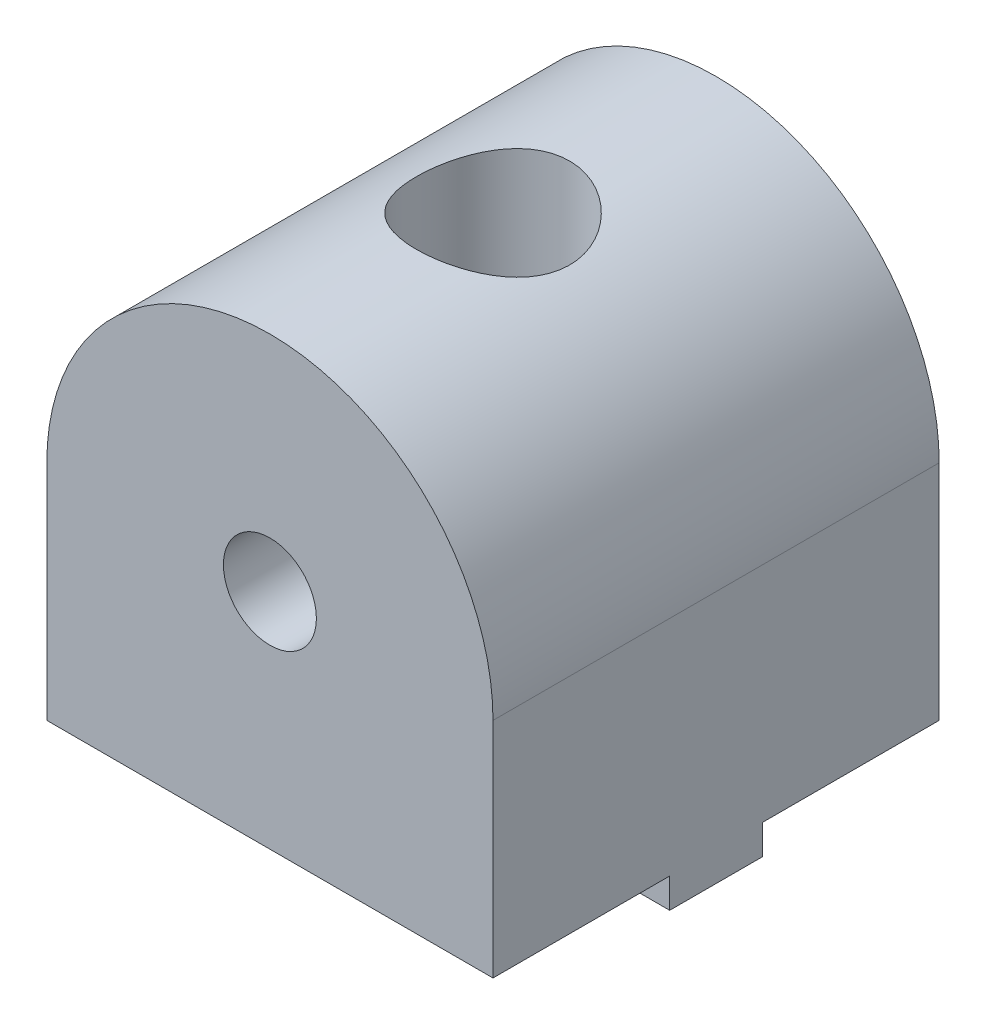
SolidWorks part; units mm, degrees
material "6105-T5 Aluminum"
ref_plane "Front Plane" through (0, 0, 0) normal (0, 0, 1) x (1, 0, 0)
ref_plane "Top Plane" through (0, 0, 0) normal (0, 1, 0) x (1, 0, 0)
ref_plane "Right Plane" through (0, 0, 0) normal (1, 0, 0) x (0, 0, -1)
sketch "Sketch1" plane through (0, 0, 0) normal (0, 0, 1) x (1, 0, 0)
  line L2 (-12.4454, 4.399) -> (-12.4454, -14.651)
  line L3 (-12.4454, -14.651) -> (25.6546, -14.651)
  line L4 (25.6546, 4.399) -> (25.6546, -14.651)
  arc A0 (25.6546, 4.399) -> (-12.4454, 4.399) centre (6.6046, 4.399) ccw
  circle A1 centre (6.6046, 4.399) radius 3.9688
  dimension "D2" = 38.1
extrude "Extrude1" add sketch "Sketch1" along normal blind 38.1
sketch "Sketch2" plane through (0, -14.651, 0) normal (0, -1, 0) x (1, 0, 0)
  line L2 (6.6046, 38.1) -> (6.6046, 0)
  line L3 (6.6046, 38.1) -> (6.6046, 0)
  circle A0 centre (6.6046, 19.05) radius 4.1656
  dimension "D1" = 19.05
extrude "Cut-Extrude1" cut sketch "Sketch2" against normal through all contours L3 A0 | L3 A0
sketch "Sketch3" plane through (0, -14.651, 0) normal (0, -1, 0) x (1, 0, 0)
  circle A0 centre (6.6046, 19.05) radius 6.5405
extrude "Cut-Extrude2" cut sketch "Sketch3" along normal blind 11.43 from offset 38.1 offset against normal yes
sketch "Sketch4" plane through (0, -14.651, 0) normal (0, -1, 0) x (1, 0, 0)
  line L2 (-4.5206, 38.1) -> (-4.5206, 0)
  line L3 (-4.5206, 23.0124) -> (-4.5206, 15.0876)
  line L12 (-12.4454, 23.0124) -> (25.6546, 23.0124)
  line L13 (-12.4454, 23.0124) -> (-4.5206, 23.0124)
  line L14 (17.7298, 15.0876) -> (25.6546, 15.0876)
  line L15 (-12.4454, 15.0876) -> (25.6546, 15.0876)
  line L16 (-12.4454, 15.0876) -> (-4.5206, 15.0876)
  line L17 (17.7298, 23.0124) -> (25.6546, 23.0124)
  line L18 (25.6546, 23.0124) -> (25.6546, 15.0876)
  line L19 (-12.4454, 23.0124) -> (-12.4454, 15.0876)
  line L22 (17.7298, 38.1) -> (17.7298, 0)
  line L23 (17.7298, 23.0124) -> (17.7298, 15.0876)
  dimension "D1" = 7.9248
  dimension "D3" = 15.0876
  dimension "D4" = 23.0124
  dimension "D5" = 7.9248
extrude "Extrude2" add sketch "Sketch4" along normal blind 2.54
